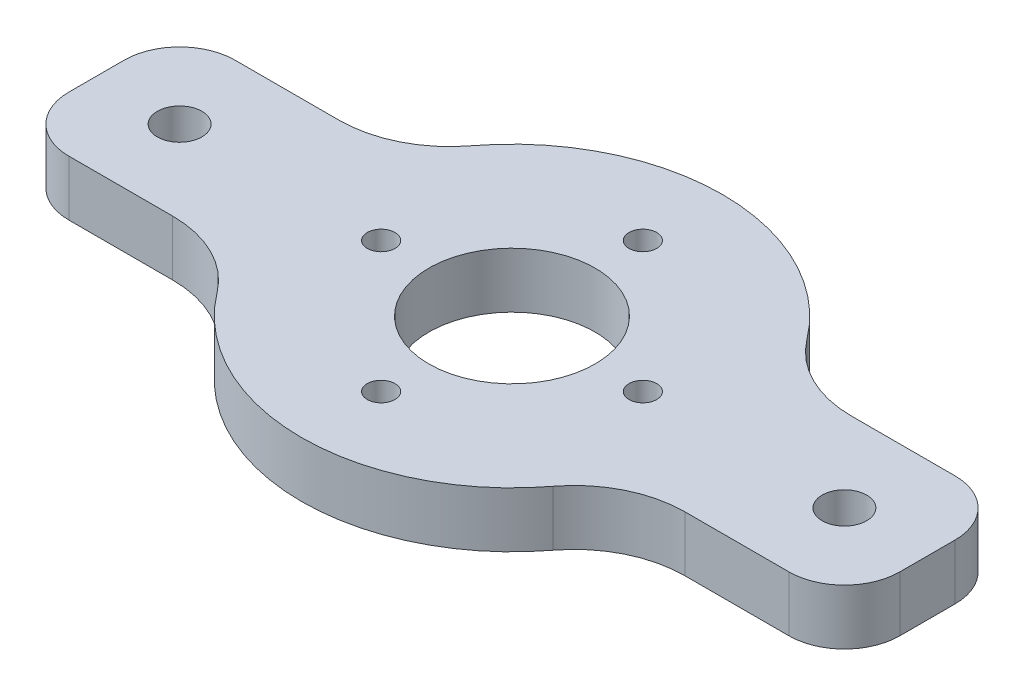
SolidWorks part; units mm, degrees
material "6061 Alloy"
ref_plane "Front Plane" through (0, 0, 0) normal (0, 0, 1) x (1, 0, 0)
ref_plane "Top Plane" through (0, 0, 0) normal (0, 1, 0) x (1, 0, 0)
ref_plane "Right Plane" through (0, 0, 0) normal (1, 0, 0) x (0, 0, -1)
sketch "Sketch1" plane through (0, 0, 0) normal (0, 1, 0) x (1, 0, 0)
  line L0 (0, 24.13) -> (0, -24.13) construction
  line L1 (-41.275, 9.525) -> (41.275, 9.525)
  line L2 (-47.625, 3.175) -> (-47.625, -3.175)
  line L3 (-41.275, -9.525) -> (41.275, -9.525)
  line L4 (47.625, 3.175) -> (47.625, -3.175)
  line L5 (-47.625, 9.525) -> (47.625, -9.525) construction
  line L6 (-47.625, -9.525) -> (47.625, 9.525) construction
  line L7 (-47.625, 0) -> (47.625, 0) construction
  circle A0 centre (0, 0) radius 15 construction
  circle A1 centre (0, 0) radius 9.525
  circle A2 centre (0, 0) radius 24.13
  circle A3 centre (15, 0) radius 1.5875
  circle A4 centre (0, -15) radius 1.5875
  circle A5 centre (-15, 0) radius 1.5875
  circle A6 centre (0, 15) radius 1.5875
  arc A7 (-29.3683, 9.525) -> (-19.2413, 14.5612) centre (-29.3683, 22.225) ccw
  arc A8 (-29.3683, -9.525) -> (-19.2413, -14.5612) centre (-29.3683, -22.225) cw
  arc A9 (29.3683, -9.525) -> (19.2413, -14.5612) centre (29.3683, -22.225) ccw
  arc A10 (29.3683, 9.525) -> (19.2413, 14.5612) centre (29.3683, 22.225) cw
  arc A11 (41.275, -9.525) -> (47.625, -3.175) centre (41.275, -3.175) ccw
  arc A12 (41.275, 9.525) -> (47.625, 3.175) centre (41.275, 3.175) cw
  arc A13 (-41.275, -9.525) -> (-47.625, -3.175) centre (-41.275, -3.175) cw
  arc A14 (-41.275, 9.525) -> (-47.625, 3.175) centre (-41.275, 3.175) ccw
  circle A15 centre (-38.1, 0) radius 2.5527
  circle A16 centre (38.1, 0) radius 2.5527
  point P16 (0, 0)
  dimension "D1" = 30
  dimension "D2" = 19.05
  dimension "D3" = 48.26
  dimension "D4" = 3.175
  dimension "D8" = 12.7
  dimension "D9" = 6.35
  dimension "D10" = 5.1054
  dimension "D6" = 19.05
  dimension "D7" = 95.25
  dimension "D11" = 38.1
  dimension "D5" = 4
extrude "Boss-Extrude2" add sketch "Sketch1" along normal blind 6.35 contours L1 A2 L3 A1 A5 | L3 A2 L1 A1 A3 | L3 A2 A4 | L1 A2 A6 | L1 A14 L2 A13 L3 A2 A15 | A12 L1 A2 L3 A11 L4 A16 | A7 L1 A2 | L3 A8 A2 | L1 A10 A2 | A9 L3 A2
